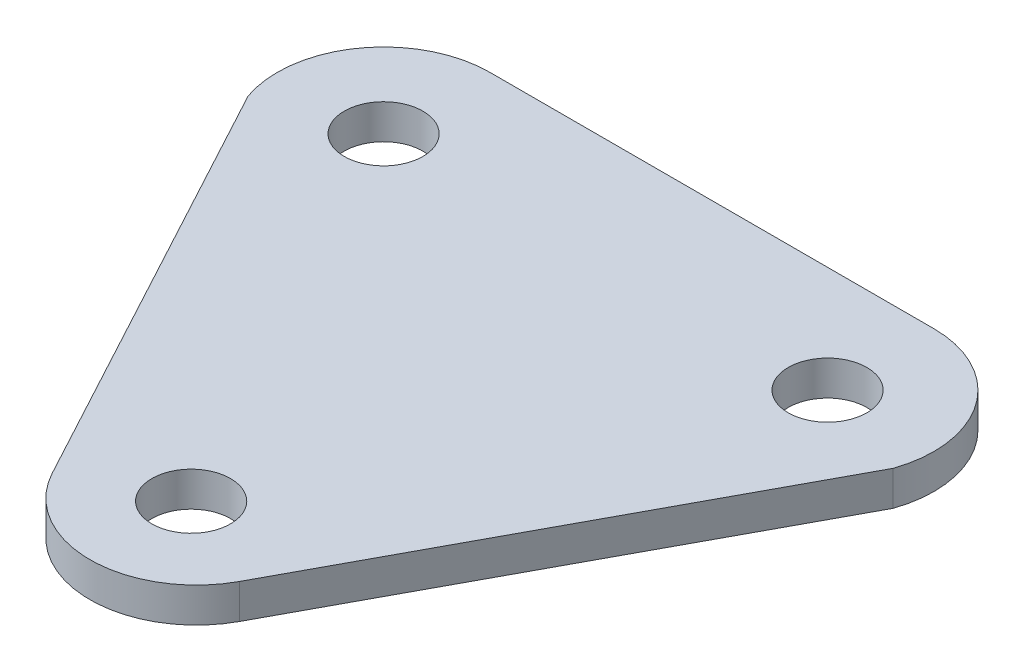
SolidWorks part; units mm, degrees
ref_plane "Front Plane" through (0, 0, 0) normal (0, 0, 1) x (1, 0, 0)
ref_plane "Top Plane" through (0, 0, 0) normal (0, 1, 0) x (1, 0, 0)
ref_plane "Right Plane" through (0, 0, 0) normal (1, 0, 0) x (0, 0, -1)
sketch "Sketch2" plane through (0, 0, 0) normal (0, 1, 0) x (1, 0, 0)
  line L0 (0, 110.3481) -> (0, -110.3481) construction
  line L1 (-48, 61.0594) -> (48, 61.0594)
  line L2 (69.723, 30.5023) -> (20.2494, -61.3476)
  line L3 (0, -73.4406) -> (0, -60.0405)
  line L4 (0, -43.0405) -> (0, 61.0594)
  line L5 (-69.723, 30.5023) -> (-20.2494, -61.3476)
  arc A0 (48, 61.0594) -> (69.723, 30.5023) centre (48, 38.0594) cw
  arc A1 (20.2494, -61.3476) -> (-20.2494, -61.3476) centre (0, -50.4406) cw
  circle A2 centre (48, 38.0594) radius 8.5
  circle A3 centre (0, -51.5405) radius 8.5
  circle A4 centre (-48, 38.0594) radius 8.5
  arc A5 (-48, 61.0594) -> (-69.723, 30.5023) centre (-48, 38.0594) ccw
  point P3 (0, 0)
  dimension "D2" = 23
  dimension "D3" = 23
  dimension "D5" = 8.5
  dimension "D6" = 17
  dimension "D1" = 48
  dimension "D4" = 88.5
extrude "Boss-Extrude1" add sketch "Sketch2" along normal blind 7.5 contours L1 A5 L5 A1 L3 A3 L4 A4 | A3 L3 A1 L2 A0 L1 L4 A2
